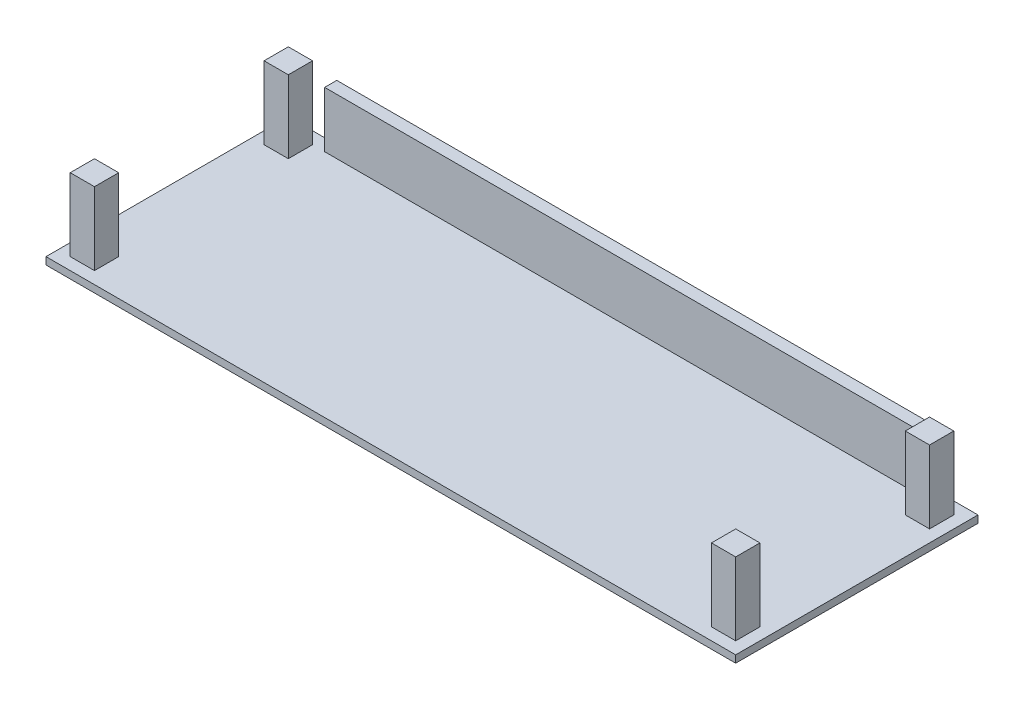
SolidWorks part; units mm, degrees
ref_plane "前视基准面" through (0, 0, 0) normal (0, 0, 1) x (1, 0, 0)
ref_plane "上视基准面" through (0, 0, 0) normal (0, 1, 0) x (1, 0, 0)
ref_plane "右视基准面" through (0, 0, 0) normal (1, 0, 0) x (0, 0, -1)
sketch "草图1" plane through (0, 0, 0) normal (0, 1, 0) x (1, 0, 0)
  line L0 (137.3205, -35) -> (137.3205, -45)
  line L1 (127.3205, -45) -> (127.3205, -35)
  line L2 (137.3205, -45) -> (127.3205, -45)
  line L3 (127.3205, -35) -> (137.3205, -35)
  line L4 (137.3205, 45) -> (127.3205, 45)
  line L5 (137.3205, 35) -> (127.3205, 35)
  line L6 (127.3205, 35) -> (127.3205, 45)
  line L7 (127.3205, 45) -> (137.3205, 45)
  line L8 (-122.3205, -50) -> (-122.3205, -30)
  line L9 (-122.3205, -30) -> (-137.3205, -30)
  line L10 (-137.3205, -30) -> (-137.3205, 30)
  line L11 (-137.3205, 30) -> (-122.3205, 30)
  line L12 (-122.3205, 30) -> (-122.3205, 45)
  line L13 (-122.3205, 45) -> (122.3205, 45)
  line L14 (122.3205, 45) -> (122.3205, 30)
  line L15 (122.3205, 30) -> (137.3205, 30)
  line L16 (137.3205, 30) -> (137.3205, -30)
  line L17 (137.3205, -30) -> (122.3205, -30)
  line L18 (122.3205, -30) -> (122.3205, -50)
  line L19 (122.3205, -50) -> (142.3205, -50)
  line L20 (142.3205, -50) -> (142.3205, 50)
  line L21 (142.3205, 50) -> (-142.3205, 50)
  line L22 (-142.3205, 50) -> (-142.3205, -50)
  line L23 (-142.3205, -50) -> (-122.3205, -50)
  line L24 (137.3205, 35) -> (137.3205, 45)
  line L25 (-127.3205, -45) -> (-137.3205, -45)
  line L26 (-127.3205, -45) -> (-127.3205, -35)
  line L27 (-127.3205, -35) -> (-137.3205, -35)
  line L28 (-137.3205, -45) -> (-137.3205, -35)
  line L29 (-137.3205, 45) -> (-127.3205, 45)
  line L30 (-137.3205, 45) -> (-137.3205, 35)
  line L31 (-137.3205, 35) -> (-127.3205, 35)
  line L32 (-127.3205, 45) -> (-127.3205, 35)
sketch "草图2" plane through (0, 0, 0) normal (0, 1, 0) x (1, 0, 0)
  line L1 (-137.3205, 45) -> (-127.3205, 45)
  line L2 (-137.3205, 45) -> (-137.3205, 35)
  line L3 (-137.3205, 35) -> (-127.3205, 35)
  line L4 (-127.3205, 45) -> (-127.3205, 35)
  line L5 (-137.3205, -35) -> (-127.3205, -35)
  line L6 (-137.3205, -35) -> (-137.3205, -45)
  line L7 (-137.3205, -45) -> (-127.3205, -45)
  line L8 (-127.3205, -35) -> (-127.3205, -45)
  line L9 (127.3205, -35) -> (137.3205, -35)
  line L10 (127.3205, -35) -> (127.3205, -45)
  line L11 (127.3205, -45) -> (137.3205, -45)
  line L12 (137.3205, -35) -> (137.3205, -45)
  line L13 (127.3205, 45) -> (137.3205, 45)
  line L14 (127.3205, 45) -> (127.3205, 35)
  line L15 (127.3205, 35) -> (137.3205, 35)
  line L16 (137.3205, 45) -> (137.3205, 35)
extrude "凸台-拉伸1" add sketch "草图2" along normal blind 30
sketch "草图3" plane through (0, 0, 0) normal (0, 1, 0) x (1, 0, 0)
  line L1 (142.3205, 50) -> (-142.3205, 50)
  line L2 (142.3205, 50) -> (142.3205, -50)
  line L3 (142.3205, -50) -> (-142.3205, -50)
  line L4 (-142.3205, 50) -> (-142.3205, -50)
extrude "凸台-拉伸2" add sketch "草图3" against normal blind 3
sketch "草图4" plane through (0, 0, 0) normal (0, 1, 0) x (1, 0, 0)
  line L6 (-122.3205, 45) -> (122.3175, 45)
  line L7 (-122.3205, 45) -> (-122.3205, 50)
  line L8 (-122.3205, 50) -> (122.3175, 50)
  line L9 (122.3175, 45) -> (122.3175, 50)
  point P10 (122.3175, 49.9006)
  dimension "D1" = 5
extrude "凸台-拉伸3" add sketch "草图4" along normal blind 23
